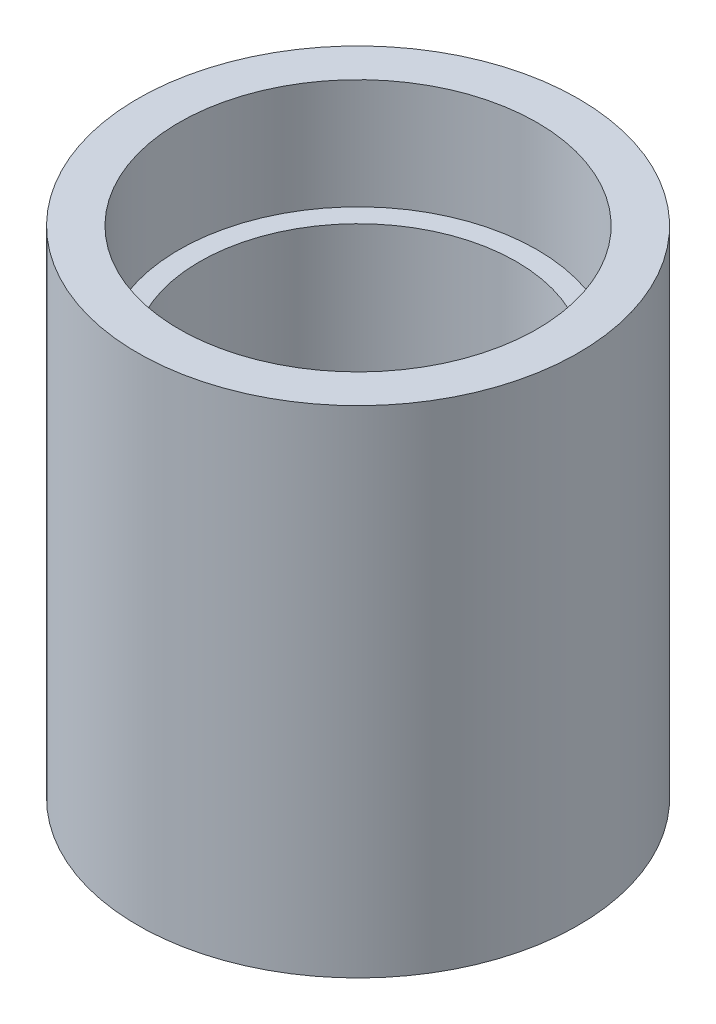
SolidWorks part; units mm, degrees
ref_plane "Alzado" through (0, 0, 0) normal (0, 0, 1) x (1, 0, 0)
ref_plane "Planta" through (0, 0, 0) normal (0, 1, 0) x (1, 0, 0)
ref_plane "Vista lateral" through (0, 0, 0) normal (1, 0, 0) x (0, 0, -1)
sketch "Croquis1" plane through (0, 0, 0) normal (0, 0, 1) x (1, 0, 0)
  line L0 (0, 0) -> (0, 99.2416) construction
  line L1 (-13, 67.9895) -> (-16, 67.9895)
  line L2 (-16, 67.9895) -> (-16, 31.9895)
  line L3 (-16, 31.9895) -> (-13, 31.9895)
  line L4 (-13, 31.9895) -> (-13, 39.9895)
  line L5 (-13, 39.9895) -> (-11.5, 39.9895)
  line L6 (-11.5, 39.9895) -> (-11.5, 59.9895)
  line L7 (-11.5, 59.9895) -> (-13, 59.9895)
  line L8 (-13, 59.9895) -> (-13, 67.9895)
  dimension "D1" = 13
  dimension "D2" = 1.5
  dimension "D3" = 16
  dimension "D4" = 1.5
  dimension "D5" = 8
  dimension "D6" = 8
  dimension "D7" = 36
revolve "Revolución1" add sketch "Croquis1" angle 360 about L0
sketch "Croquis2" plane through (0, 67.9895, 0) normal (0, 1, 0) x (1, 0, 0)
  line L1 (-20, -20.7664) -> (20, -20.7664)
  line L2 (-20, -20.7664) -> (-20, 20.7664)
  line L3 (-20, 20.7664) -> (20, 20.7664)
  line L4 (20, -20.7664) -> (20, 20.7664)
  line L5 (-20, -20.7664) -> (20, 20.7664) construction
  line L6 (-20, 20.7664) -> (20, -20.7664) construction
  point P0 (0, 0)
  dimension "D1" = 40
